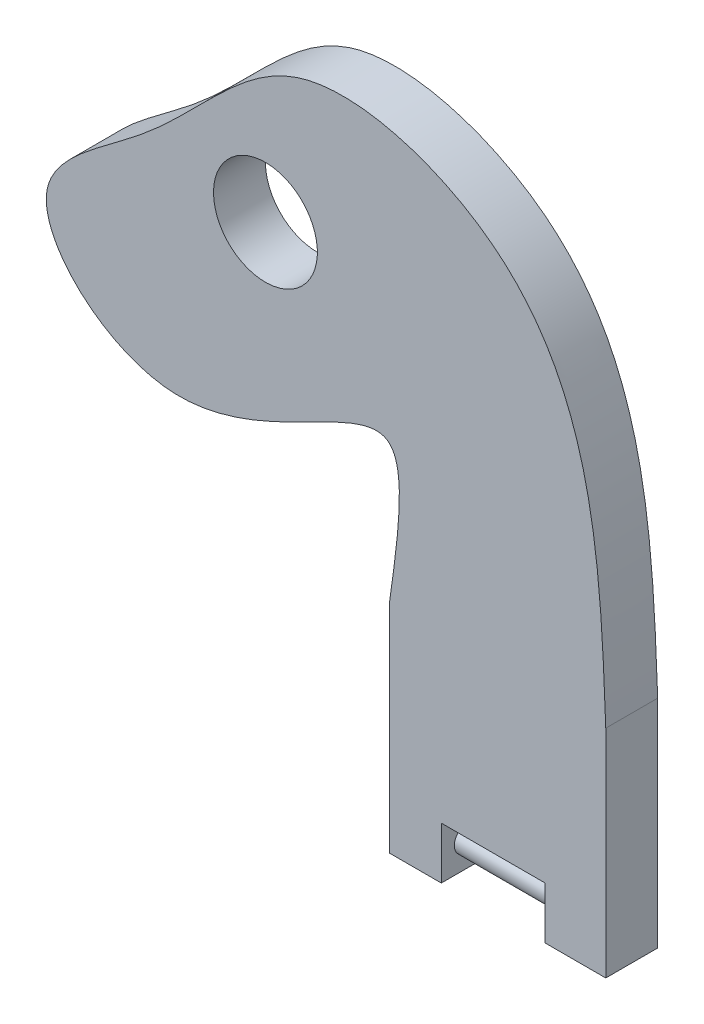
SolidWorks part; units mm, degrees
ref_plane "Alzado" through (0, 0, 0) normal (0, 0, 1) x (1, 0, 0)
ref_plane "Planta" through (0, 0, 0) normal (0, 1, 0) x (1, 0, 0)
ref_plane "Vista lateral" through (0, 0, 0) normal (1, 0, 0) x (0, 0, -1)
sketch "Croquis1" plane through (0, 0, 0) normal (0, 0, 1) x (1, 0, 0)
  line L4 (-25.1765, -24.9241) -> (-25.1765, 0.0759)
  line L5 (-0.1765, -24.9241) -> (-25.1765, -24.9241)
  line L6 (-0.1765, 0.0759) -> (-0.1765, -24.9241)
  circle A1 centre (-39.4974, 31.0299) radius 6
  spline S1 degree 3 poles (-25.1765, 0.0759) (-24.1778, 7.153) (-21.5314, 25.9054) (-48.1677, -0.1612) (-71.3264, 21.6944) (-49.6927, 33.7595) (-37.9229, 52.371) (-1.7888, 41.1703) (-0.8183, 16.4329) (-0.1765, 0.0759) knots 0 0 0 0 0.095474 0.252977 0.36642 0.461159 0.604149 0.738254 1 1 1 1
  point P0 (0, 0)
  dimension "D3" = 12
  dimension "D4" = 25
  dimension "D2" = 25
  dimension "D5" = 25
extrude "Saliente-Extruir1" add sketch "Croquis1" along normal blind 6
sketch "Croquis2" plane through (0, 0, 6) normal (0, 0, 1) x (1, 0, 0)
  line L0 (-25.1765, -24.9241) -> (-0.1765, -24.9241) construction
  line L1 (-19.1765, -24.9241) -> (-7.1765, -24.9241)
  line L2 (-19.1765, -24.9241) -> (-19.1765, -18.9241)
  line L3 (-19.1765, -18.9241) -> (-7.1765, -18.9241)
  line L4 (-7.1765, -24.9241) -> (-7.1765, -18.9241)
  line L5 (-25.1765, 0.0759) -> (-25.1765, -24.9241) construction
  dimension "D1" = 6
  dimension "D2" = 12
  dimension "D3" = 6
extrude "Cortar-Extruir1" cut sketch "Croquis2" against normal blind 10
sketch "Croquis3" plane through (-7.1765, 0, 0) normal (-1, 0, 0) x (0, 0, 1)
  line L0 (0, -18.9241) -> (0, -24.9241) construction
  line L1 (0, -24.9241) -> (6, -24.9241) construction
  circle A0 centre (3, -21.9241) radius 1.5
  dimension "D1" = 3
  dimension "D2" = 3
  dimension "D3" = 3
extrude "Saliente-Extruir2" add sketch "Croquis3" along normal up to next
